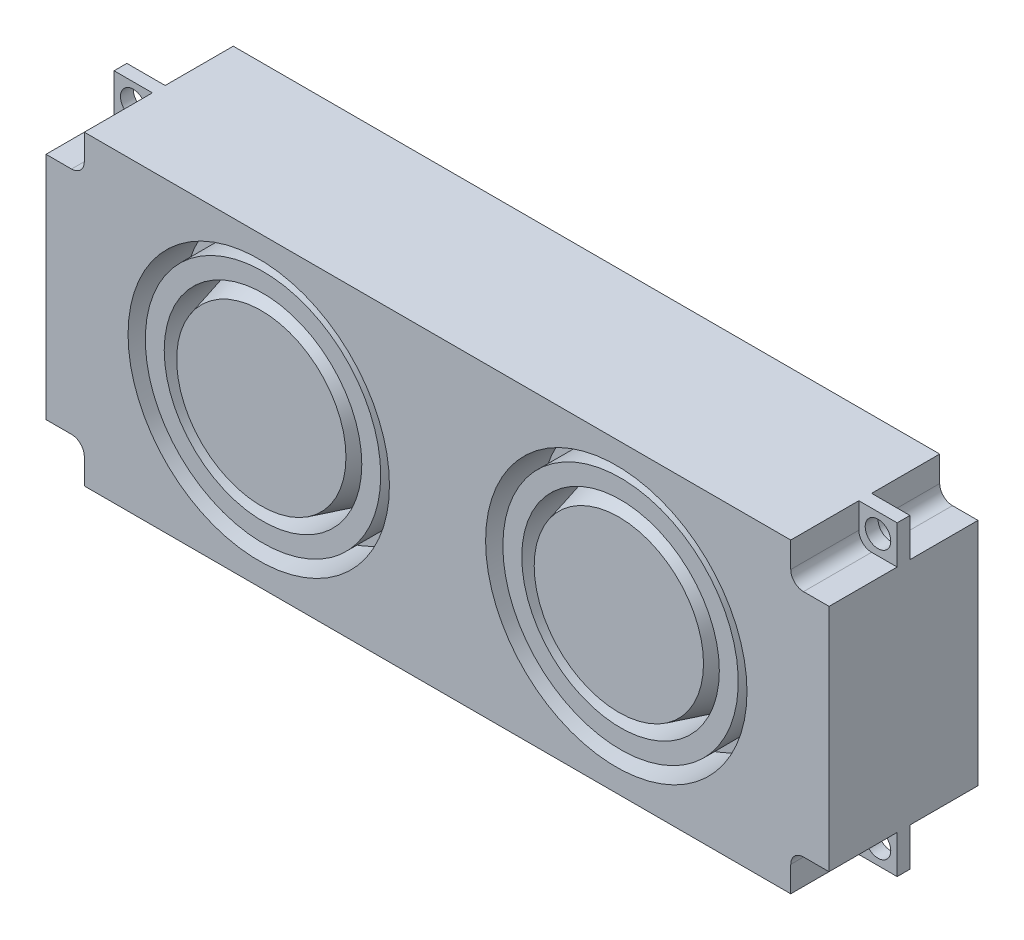
SolidWorks part; units mm, degrees
other "Camera1"
ref_plane "Front Plane" through (0, 0, 0) normal (0, 0, 1) x (1, 0, 0)
ref_plane "Top Plane" through (0, 0, 0) normal (0, 1, 0) x (1, 0, 0)
ref_plane "Right Plane" through (0, 0, 0) normal (1, 0, 0) x (0, 0, -1)
sketch "Sketch1" plane through (0, 0, 0) normal (0, 0, 1) x (1, 0, 0)
  line L1 (-46, -18) -> (46, -18)
  line L2 (-46, -18) -> (-46, 18)
  line L3 (-46, 18) -> (46, 18)
  line L4 (46, -18) -> (46, 18)
  line L5 (-46, -18) -> (46, 18) construction
  line L6 (-46, 18) -> (46, -18) construction
  point P0 (0, 0)
  dimension "D1" = 92
  dimension "D2" = 36
extrude "Boss-Extrude1" add sketch "Sketch1" along normal mid plane 17.5
sketch "Sketch2" plane through (0, 0, 8.75) normal (0, 0, 1) x (1, 0, 0)
  line L0 (-46, 18) -> (-46, -18) construction
  line L1 (46, 18) -> (-46, 18) construction
  line L2 (0, -9.625) -> (0, 9.625) construction
  line L3 (-46, 18) -> (-41.5, 18)
  line L4 (-46, 18) -> (-46, 13.5)
  line L5 (-46, 13.5) -> (-43, 13.5)
  line L6 (-41.5, 18) -> (-41.5, 15)
  line L7 (46, 13.5) -> (43, 13.5)
  line L8 (41.5, 18) -> (41.5, 15)
  line L9 (46, 18) -> (46, 13.5)
  line L10 (46, 18) -> (41.5, 18)
  line L11 (9.625, 0) -> (-9.625, 0) construction
  line L12 (46, -18) -> (41.5, -18)
  line L13 (46, -18) -> (46, -13.5)
  line L14 (41.5, -18) -> (41.5, -15)
  line L15 (46, -13.5) -> (43, -13.5)
  line L16 (-41.5, -18) -> (-41.5, -15)
  line L17 (-46, -13.5) -> (-43, -13.5)
  line L18 (-46, -18) -> (-46, -13.5)
  line L19 (-46, -18) -> (-41.5, -18)
  circle A0 centre (-43.75, 15.75) radius 1.5
  arc A1 (-43, 13.5) -> (-41.5, 15) centre (-43, 15) ccw
  arc A2 (43, 13.5) -> (41.5, 15) centre (43, 15) cw
  circle A3 centre (43.75, 15.75) radius 1.5
  circle A4 centre (43.75, -15.75) radius 1.5
  arc A5 (43, -13.5) -> (41.5, -15) centre (43, -15) ccw
  arc A6 (-43, -13.5) -> (-41.5, -15) centre (-43, -15) cw
  circle A7 centre (-43.75, -15.75) radius 1.5
  dimension "D1" = 2.25
  dimension "D4" = 1.5
  dimension "D2" = 2.25
  dimension "D3" = 2.25
extrude "Cut-Extrude1" cut sketch "Sketch2" against normal through all both and the other way through all contours A3 | A4 | A7 | A0
sketch "Sketch3" plane through (0, 0, 8.75) normal (0, 0, 1) x (1, 0, 0)
  line L4 (-41.5, 18) -> (-46, 18)
  line L5 (-41.5, 15) -> (-41.5, 18)
  line L6 (-46, 13.5) -> (-43, 13.5)
  line L7 (-46, 18) -> (-46, 13.5)
  line L8 (-41.5, 18) -> (-46, 18)
  line L9 (-41.5, 15) -> (-41.5, 18)
  line L10 (-46, 13.5) -> (-43, 13.5)
  line L11 (-46, 18) -> (-46, 13.5)
  line L12 (41.5, 18) -> (41.5, 15)
  line L13 (46, 18) -> (41.5, 18)
  line L14 (46, 13.5) -> (46, 18)
  line L15 (43, 13.5) -> (46, 13.5)
  line L16 (41.5, 18) -> (41.5, 15)
  line L17 (46, 18) -> (41.5, 18)
  line L18 (46, 13.5) -> (46, 18)
  line L19 (43, 13.5) -> (46, 13.5)
  line L20 (-41.5, -18) -> (-41.5, -15)
  line L21 (-43, -13.5) -> (-46, -13.5)
  line L22 (-46, -13.5) -> (-46, -18)
  line L23 (-46, -18) -> (-41.5, -18)
  line L24 (-41.5, -18) -> (-41.5, -15)
  line L25 (-43, -13.5) -> (-46, -13.5)
  line L26 (-46, -13.5) -> (-46, -18)
  line L27 (-46, -18) -> (-41.5, -18)
  line L28 (41.5, -18) -> (46, -18)
  line L29 (41.5, -15) -> (41.5, -18)
  line L30 (46, -13.5) -> (43, -13.5)
  line L31 (46, -18) -> (46, -13.5)
  line L32 (41.5, -18) -> (46, -18)
  line L33 (41.5, -15) -> (41.5, -18)
  line L34 (46, -13.5) -> (43, -13.5)
  line L35 (46, -18) -> (46, -13.5)
  circle A1 centre (-43.75, 15.75) radius 1.5
  circle A2 centre (-43.75, 15.75) radius 1.5
  arc A3 (-43, 13.5) -> (-41.5, 15) centre (-43, 15) ccw
  arc A4 (-43, 13.5) -> (-41.5, 15) centre (-43, 15) ccw
  circle A5 centre (43.75, -15.75) radius 1.5
  circle A6 centre (43.75, -15.75) radius 1.5
  circle A7 centre (43.75, 15.75) radius 1.5
  circle A8 centre (43.75, 15.75) radius 1.5
  arc A9 (41.5, 15) -> (43, 13.5) centre (43, 15) ccw
  arc A10 (41.5, 15) -> (43, 13.5) centre (43, 15) ccw
  circle A11 centre (-43.75, -15.75) radius 1.5
  circle A12 centre (-43.75, -15.75) radius 1.5
  arc A13 (-41.5, -15) -> (-43, -13.5) centre (-43, -15) ccw
  arc A14 (-41.5, -15) -> (-43, -13.5) centre (-43, -15) ccw
  arc A15 (43, -13.5) -> (41.5, -15) centre (43, -15) ccw
  arc A16 (43, -13.5) -> (41.5, -15) centre (43, -15) ccw
  dimension "D1" = 0
  dimension "D2" = 0
  dimension "D3" = 0
  dimension "D4" = 0
  dimension "D5" = 0
  dimension "D6" = 0
  dimension "D7" = 0
  dimension "D8" = 0
extrude "Cut-Extrude2" cut sketch "Sketch3" against normal blind 8
sketch "Sketch4" plane through (0, 0, -8.75) normal (0, 0, -1) x (-1, 0, 0)
  line L4 (46, 18) -> (41.5, 18)
  line L5 (41.5, 18) -> (41.5, 15)
  line L6 (43, 13.5) -> (46, 13.5)
  line L7 (46, 13.5) -> (46, 18)
  line L8 (46, 18) -> (41.5, 18)
  line L9 (41.5, 18) -> (41.5, 15)
  line L10 (43, 13.5) -> (46, 13.5)
  line L11 (46, 13.5) -> (46, 18)
  line L12 (-41.5, 15) -> (-41.5, 18)
  line L13 (-41.5, 18) -> (-46, 18)
  line L14 (-46, 18) -> (-46, 13.5)
  line L15 (-46, 13.5) -> (-43, 13.5)
  line L16 (-41.5, 15) -> (-41.5, 18)
  line L17 (-41.5, 18) -> (-46, 18)
  line L18 (-46, 18) -> (-46, 13.5)
  line L19 (-46, 13.5) -> (-43, 13.5)
  line L20 (41.5, -15) -> (41.5, -18)
  line L21 (46, -13.5) -> (43, -13.5)
  line L22 (46, -18) -> (46, -13.5)
  line L23 (41.5, -18) -> (46, -18)
  line L24 (41.5, -15) -> (41.5, -18)
  line L25 (46, -13.5) -> (43, -13.5)
  line L26 (46, -18) -> (46, -13.5)
  line L27 (41.5, -18) -> (46, -18)
  line L28 (-46, -18) -> (-41.5, -18)
  line L29 (-41.5, -18) -> (-41.5, -15)
  line L30 (-43, -13.5) -> (-46, -13.5)
  line L31 (-46, -13.5) -> (-46, -18)
  line L32 (-46, -18) -> (-41.5, -18)
  line L33 (-41.5, -18) -> (-41.5, -15)
  line L34 (-43, -13.5) -> (-46, -13.5)
  line L35 (-46, -13.5) -> (-46, -18)
  circle A1 centre (43.75, 15.75) radius 1.5
  circle A2 centre (43.75, 15.75) radius 1.5
  arc A3 (41.5, 15) -> (43, 13.5) centre (43, 15) ccw
  arc A4 (41.5, 15) -> (43, 13.5) centre (43, 15) ccw
  circle A5 centre (-43.75, -15.75) radius 1.5
  circle A6 centre (-43.75, -15.75) radius 1.5
  circle A7 centre (-43.75, 15.75) radius 1.5
  circle A8 centre (-43.75, 15.75) radius 1.5
  arc A9 (-43, 13.5) -> (-41.5, 15) centre (-43, 15) ccw
  arc A10 (-43, 13.5) -> (-41.5, 15) centre (-43, 15) ccw
  circle A11 centre (43.75, -15.75) radius 1.5
  circle A12 centre (43.75, -15.75) radius 1.5
  arc A13 (43, -13.5) -> (41.5, -15) centre (43, -15) ccw
  arc A14 (43, -13.5) -> (41.5, -15) centre (43, -15) ccw
  arc A15 (-41.5, -15) -> (-43, -13.5) centre (-43, -15) ccw
  arc A16 (-41.5, -15) -> (-43, -13.5) centre (-43, -15) ccw
  dimension "D1" = 0
  dimension "D2" = 0
  dimension "D3" = 0
  dimension "D4" = 0
  dimension "D5" = 0
  dimension "D6" = 0
  dimension "D7" = 0
  dimension "D8" = 0
extrude "Cut-Extrude3" cut sketch "Sketch4" against normal blind 8
sketch "Sketch5" plane through (0, 0, 8.75) normal (0, 0, 1) x (1, 0, 0)
  line L0 (-21.0036, 0) -> (0, 0) construction
  line L1 (0, 0) -> (21.0036, 0) construction
  circle A0 centre (-21.0036, 0) radius 15.3554
  circle A1 centre (21.0036, 0) radius 15.3554
extrude "Cut-Extrude4" cut sketch "Sketch5" against normal blind 6.5
sketch "Sketch6" plane through (0, 0, 2.25) normal (0, 0, 1) x (1, 0, 0)
  circle A0 centre (-21.0036, 0) radius 13.8291
  circle A1 centre (-21.0036, 0) radius 11.6073
extrude "Boss-Extrude2" add sketch "Sketch6" along normal blind 6
sketch "Sketch7" plane through (0, 0, 2.25) normal (0, 0, 1) x (1, 0, 0)
  circle A1 centre (-21.0036, 0) radius 11.6073
  circle A2 centre (-21.0036, 0) radius 11.6073
  dimension "D1" = 0
extrude "Boss-Extrude3" add sketch "Sketch7" along normal blind 6.2 draft 15
mirror "Mirror2" about plane through (0, 0, 0) normal (1, 0, 0) of "Boss-Extrude2", "Boss-Extrude3"
